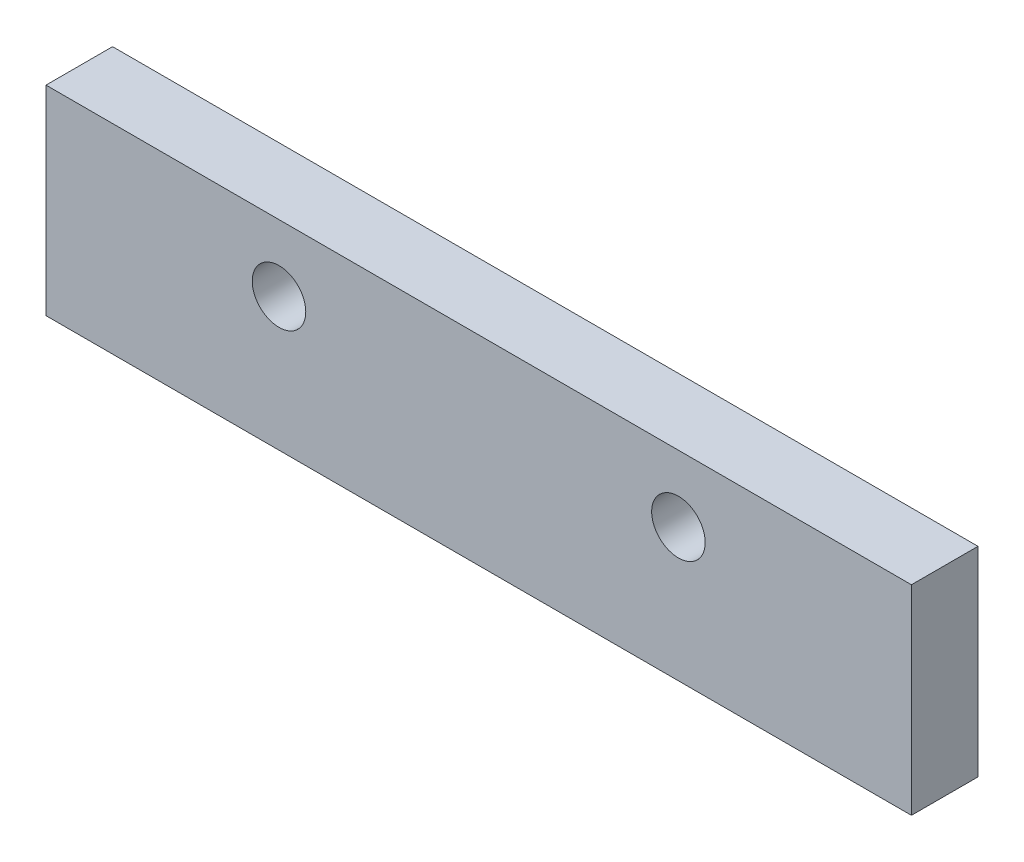
SolidWorks part; units mm, degrees
material "6061 Alloy"
ref_plane "Front Plane" through (0, 0, 0) normal (0, 0, 1) x (1, 0, 0)
ref_plane "Top Plane" through (0, 0, 0) normal (0, 1, 0) x (1, 0, 0)
ref_plane "Right Plane" through (0, 0, 0) normal (1, 0, 0) x (0, 0, -1)
sketch "Sketch1" plane through (0, 0, 0) normal (0, 0, 1) x (1, 0, 0)
  line L1 (0, 0) -> (82.55, 0)
  line L2 (0, 0) -> (0, 19.05)
  line L3 (0, 19.05) -> (82.55, 19.05)
  line L4 (82.55, 0) -> (82.55, 19.05)
  dimension "D1" = 82.55
  dimension "D2" = 19.05
extrude "Boss-Extrude1" add sketch "Sketch1" against normal blind 6.35
hole_wizard "1/4-20 Tapped Hole1" positions "Sketch2" profile "Sketch3" tap size "1/4-20" standard "ANSI Inch" end condition through all
sketch "Sketch2" plane through (0, 0, 0) normal (0, 0, 1) x (1, 0, 0)
  line L0 (82.55, 19.05) -> (0, 19.05) construction
  line L1 (0, 19.05) -> (0, 0) construction
  line L2 (82.55, 0) -> (82.55, 19.05) construction
  point P0 (22.225, 12.7)
  point P7 (60.325, 12.7)
  dimension "D1" = 6.35
  dimension "D2" = 22.225
  dimension "D3" = 6.35
  dimension "D4" = 22.225
sketch "Sketch3" plane through (22.225, 12.7, 0) normal (1, 0, 0) x (0, -1, 0)
  line L0 (0, 0) -> (0, 6.35)
  line L1 (0, 6.35) -> (2.5527, 6.35)
  line L2 (2.5527, 6.35) -> (2.5527, 0)
  line L5 (2.5527, 0) -> (0, 0)
  line L11 (0, -6.35) -> (0, 107.95) construction
  dimension "Thru Tap Drill Dia." = 5.1054
  dimension "Thru Tap Drill Depth" = 6.35
cosmetic thread "Hole Thread1"
cosmetic thread "Hole Thread2"
